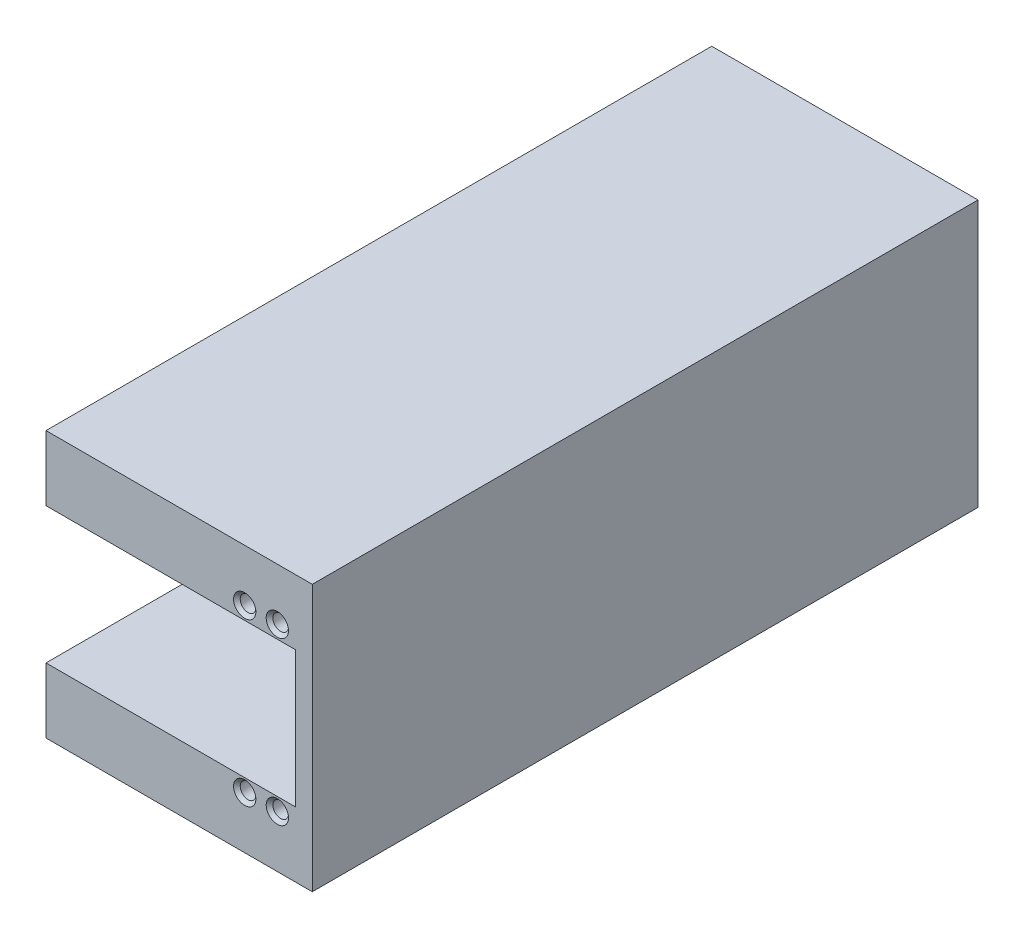
SolidWorks part; units mm, degrees
material "ABS"
ref_plane "Front Plane" through (0, 0, 0) normal (0, 0, 1) x (1, 0, 0)
ref_plane "Top Plane" through (0, 0, 0) normal (0, 1, 0) x (1, 0, 0)
ref_plane "Right Plane" through (0, 0, 0) normal (1, 0, 0) x (0, 0, -1)
sketch "Sketch1" plane through (0, 0, 0) normal (0, 0, 1) x (1, 0, 0)
  line L0 (-40, 40) -> (40, 40)
  line L1 (-40, 40) -> (40, 40) construction
  line L2 (-40, 40) -> (-40, -40) construction
  line L3 (-40, -40) -> (40, -40) construction
  line L4 (40, 40) -> (40, -40) construction
  line L5 (-40, 40) -> (40, -40) construction
  line L6 (-40, -40) -> (40, 40) construction
  line L7 (40, 40) -> (40, -40)
  line L8 (40, -40) -> (-40, -40)
  line L9 (-40, -40) -> (-40, -20.45)
  line L10 (-40, -20.45) -> (35, -20.45)
  line L11 (35, -20.45) -> (35, 20.45)
  line L12 (35, 20.45) -> (-40, 20.45)
  line L13 (-40, 20.45) -> (-40, 40)
  point P0 (0, 0)
  dimension "D1" = 80
  dimension "D2" = 80
  dimension "D3" = 40.9
  dimension "D5" = 5
extrude "Boss-Extrude1" add sketch "Sketch1" along normal blind 200
sketch "Sketch2" plane through (0, 0, 200) normal (0, 0, 1) x (1, 0, 0)
  line L0 (35, 20.45) -> (14.2, 20.45) construction
  line L1 (-40, 20.45) -> (35, 20.45) construction
  line L2 (24.6, 20.45) -> (24.6, 24.34) construction
  line L3 (24.6, 24.34) -> (29.5, 24.34) construction
  line L4 (35, 20.45) -> (35, -20.45) construction
  line L5 (35, 0) -> (40, 0) construction
  line L6 (40, -40) -> (40, 40) construction
  circle A0 centre (29.5, 24.34) radius 2.35
  circle A1 centre (19.7, 24.34) radius 2.35
  circle A2 centre (19.7, -24.34) radius 2.35
  circle A3 centre (29.5, -24.34) radius 2.35
  dimension "D4" = 4.7
  dimension "D1" = 20.8
  dimension "D2" = 3.89
  dimension "D3" = 4.9
extrude "Cut-Extrude1" cut sketch "Sketch2" against normal blind 8
sketch "Sketch3" plane through (0, 0, 0) normal (0, 0, -1) x (-1, 0, 0)
  line L0 (-35, 20.45) -> (-14.2, 20.45) construction
  line L1 (40, 20.45) -> (-35, 20.45) construction
  line L2 (-35, 20.45) -> (-35, -20.45) construction
  line L3 (-35, 0) -> (-40, 0) construction
  line L4 (-40, -40) -> (-40, 40) construction
  line L5 (-24.6, 20.45) -> (-24.6, 24.34) construction
  line L6 (-24.6, 24.34) -> (-29.5, 24.34) construction
  circle A0 centre (-29.5, 24.34) radius 2.35
  circle A1 centre (-19.7, 24.34) radius 2.35
  circle A2 centre (-19.7, -24.34) radius 2.35
  circle A3 centre (-29.5, -24.34) radius 2.35
  dimension "D4" = 4.7
  dimension "D1" = 20.8
  dimension "D2" = 3.89
  dimension "D3" = 4.9
extrude "Cut-Extrude2" cut sketch "Sketch3" against normal blind 8
chamfer "Chamfer1" distance 1 angle 45 8 edges at (17.35, -24.34, 0) (31.85, -24.34, 0) (27.15, 24.34, 0) (22.05, 24.34, 0) (27.15, -24.34, 200) (22.05, -24.34, 200) (17.35, 24.34, 200) (31.85, 24.34, 200)
